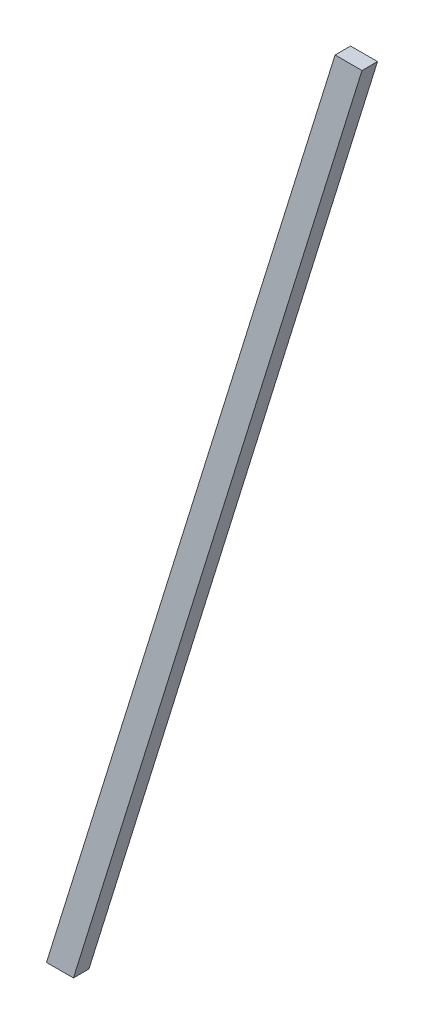
SolidWorks part; units mm, degrees
ref_plane "Front Plane" through (0, 0, 0) normal (0, 0, 1) x (1, 0, 0)
ref_plane "Top Plane" through (0, 0, 0) normal (0, 1, 0) x (1, 0, 0)
ref_plane "Right Plane" through (0, 0, 0) normal (1, 0, 0) x (0, 0, -1)
sketch "Sketch1" plane through (0, 0, 0) normal (0, 0, 1) x (1, 0, 0)
  line L0 (5.6775, 548.4656) -> (23.0608, 548.4656)
  line L1 (23.0608, 548.4656) -> (-163.0909, -51.5344)
  line L2 (-163.0909, -51.5344) -> (-180.4742, -51.5344)
  line L3 (-180.4742, -51.5344) -> (5.6775, 548.4656)
  point P2 (-180.4742, -51.5344)
  dimension "D1" = 17.3833
  dimension "D2" = 600
extrude "Boss-Extrude1" add sketch "Sketch1" along normal blind 10
